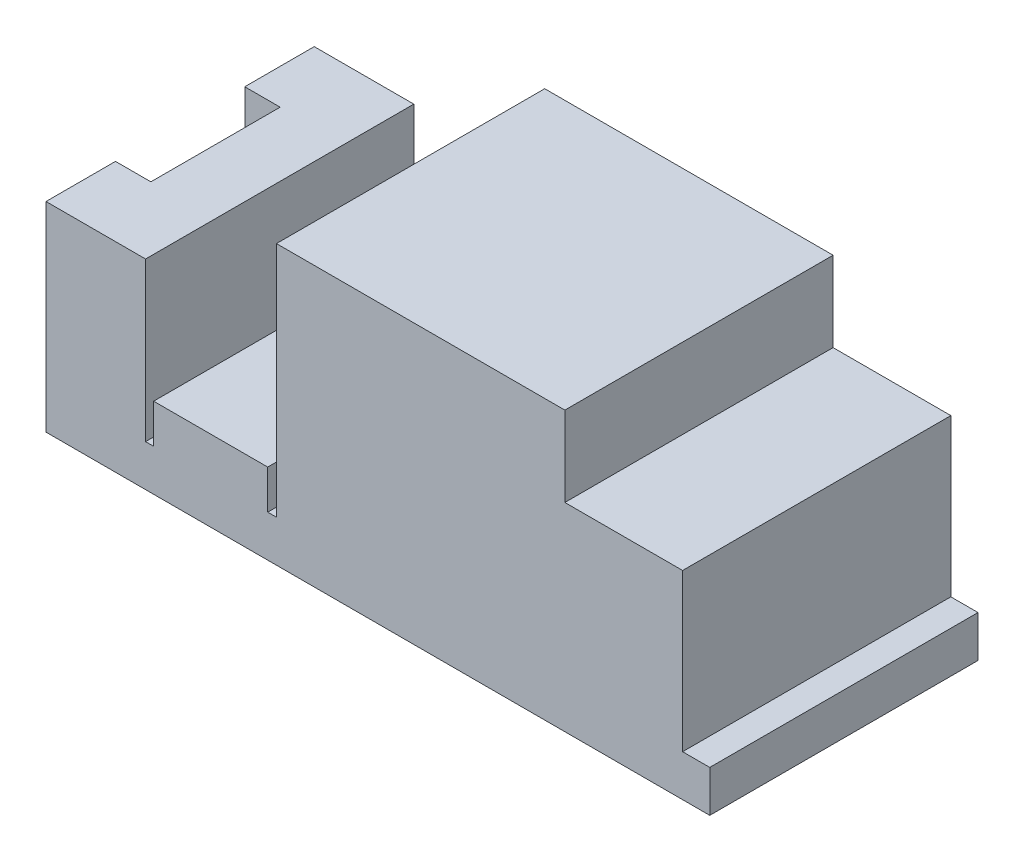
SolidWorks part; units mm, degrees
ref_plane "Front Plane" through (0, 0, 0) normal (0, 0, 1) x (1, 0, 0)
ref_plane "Top Plane" through (0, 0, 0) normal (0, 1, 0) x (1, 0, 0)
ref_plane "Right Plane" through (0, 0, 0) normal (1, 0, 0) x (0, 0, -1)
sketch "Sketch1" plane through (0, 0, 0) normal (0, 1, 0) x (1, 0, 0)
  line L1 (-21.565, 8.715) -> (21.565, 8.715)
  line L2 (-21.565, 8.715) -> (-21.565, -8.715)
  line L3 (-21.565, -8.715) -> (21.565, -8.715)
  line L4 (21.565, 8.715) -> (21.565, -8.715)
  line L5 (0, -8.715) -> (0, 8.715) construction
  line L6 (-21.565, 0) -> (21.565, 0) construction
  point P0 (0, 0)
extrude "Boss-Extrude1" add sketch "Sketch1" against normal blind 2.7
sketch "Sketch2" plane through (0, 0, 0) normal (0, 1, 0) x (1, 0, 0)
  line L0 (-21.565, 8.715) -> (-21.565, -8.715)
  line L1 (-21.565, 8.715) -> (-15.095, 8.715)
  line L2 (-21.565, -8.715) -> (-15.095, -8.715)
  line L3 (-15.095, 8.715) -> (-15.095, -8.715)
extrude "Boss-Extrude2" add sketch "Sketch2" along normal blind 10.28
sketch "Sketch3" plane through (0, 0, 0) normal (0, 1, 0) x (1, 0, 0)
  line L0 (21.565, 8.715) -> (19.8002, 8.715)
  line L1 (21.565, 8.715) -> (-15.095, 8.715) construction
  line L2 (19.8002, 8.715) -> (19.8002, -8.715)
  line L3 (19.8002, 8.715) -> (12.1502, 8.715)
  line L4 (19.8002, -8.715) -> (12.1502, -8.715)
  line L5 (12.1502, 8.715) -> (12.1502, -8.715)
  line L6 (-15.095, -8.715) -> (21.565, -8.715) construction
  line M6 (-15.095, -8.715) -> (21.565, -8.715)
  line M8 (21.565, 8.715) -> (-15.095, 8.715)
extrude "Boss-Extrude3" add sketch "Sketch3" along normal blind 10.2 contours L5 L2 M8 M6
sketch "Sketch4" plane through (0, 0, 0) normal (0, 1, 0) x (1, 0, 0)
  line L0 (12.1502, 8.715) -> (12.1502, -8.715)
  line L1 (12.1502, 8.715) -> (-6.5898, 8.715)
  line L2 (12.1502, -8.715) -> (-6.5898, -8.715)
  line L3 (-6.5898, 8.715) -> (-6.5898, -8.715)
  line L4 (12.1502, 8.715) -> (12.1502, -8.715) construction
  line L5 (-15.095, -8.715) -> (12.1502, -8.715) construction
extrude "Boss-Extrude4" add sketch "Sketch4" along normal blind 15.4
sketch "Sketch5" plane through (0, 0, 0) normal (0, 1, 0) x (1, 0, 0)
  line L0 (-14.5702, 8.715) -> (-14.5702, -8.715)
  line L1 (-14.5702, 8.715) -> (-7.159, 8.715)
  line L2 (-14.5702, -8.715) -> (-7.159, -8.715)
  line L3 (-7.159, 8.715) -> (-7.159, -8.715)
  line L4 (-6.5898, 8.715) -> (-15.095, 8.715) construction
  line L5 (-15.095, -8.715) -> (-6.5898, -8.715) construction
extrude "Boss-Extrude5" add sketch "Sketch5" along normal blind 2.54
sketch "Sketch6" plane through (-21.565, 0, 0) normal (-1, 0, 0) x (0, 0, 1)
  line L0 (-4.2, 0) -> (4.2, 0)
  line L2 (9.5865, 0) -> (-9.5865, 0) construction
  line L3 (-8.715, 10.28) -> (8.715, 10.28) construction
  line L5 (-4.2, 0) -> (-4.2, 10.28)
  line L6 (-4.2, 10.28) -> (4.2, 10.28)
  line L7 (4.2, 0) -> (4.2, 10.28)
  point P4 (0, 0)
extrude "Cut-Extrude1" cut sketch "Sketch6" against normal blind 2.3
